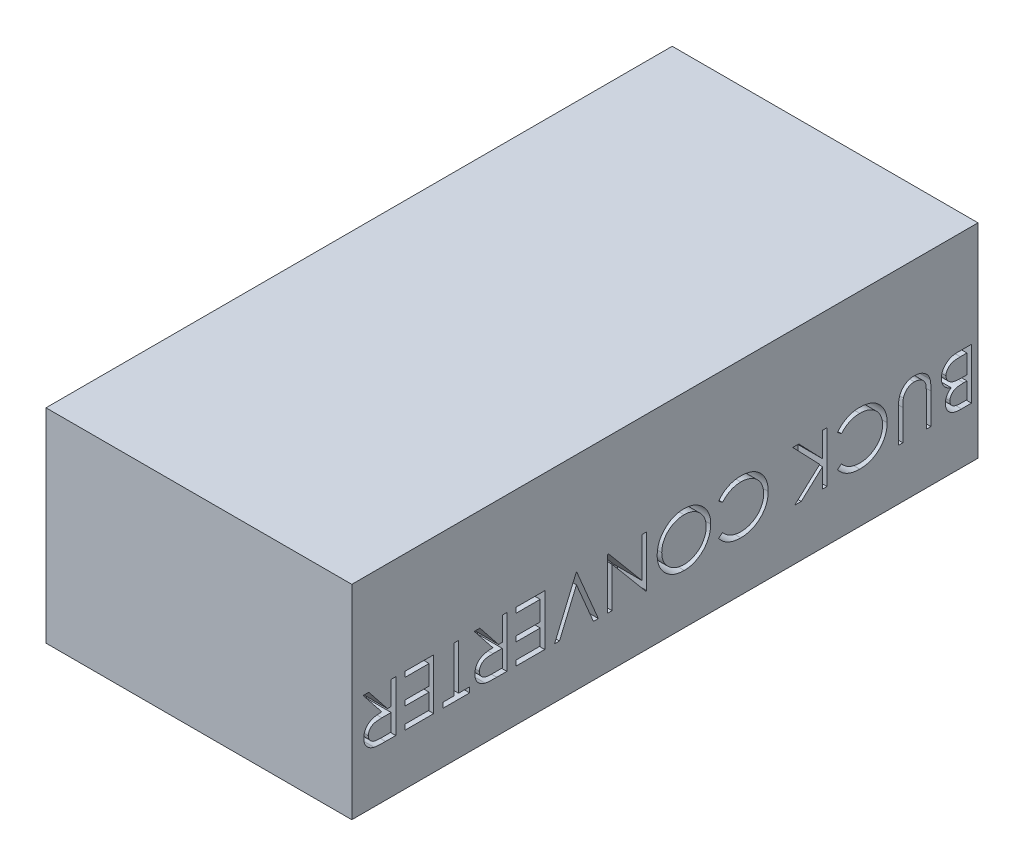
SolidWorks part; units mm, degrees
ref_plane "Front Plane" through (0, 0, 0) normal (0, 0, 1) x (1, 0, 0)
ref_plane "Top Plane" through (0, 0, 0) normal (0, 1, 0) x (1, 0, 0)
ref_plane "Right Plane" through (0, 0, 0) normal (1, 0, 0) x (0, 0, -1)
sketch "Sketch1" plane through (0, 0, 0) normal (0, 1, 0) x (1, 0, 0)
  line L1 (-10.5, -21.5) -> (10.5, -21.5)
  line L2 (-10.5, -21.5) -> (-10.5, 21.5)
  line L3 (-10.5, 21.5) -> (10.5, 21.5)
  line L4 (10.5, -21.5) -> (10.5, 21.5)
  line L5 (-10.5, -21.5) -> (10.5, 21.5) construction
  line L6 (-10.5, 21.5) -> (10.5, -21.5) construction
  point P0 (0, 0)
  dimension "D1" = 21
  dimension "D2" = 43
extrude "Boss-Extrude1" add sketch "Sketch1" along normal blind 14
sketch "Sketch2" plane through (10.5, 0, 0) normal (1, 0, 0) x (0, 0, -1)
  line L0 (21.5, 7) -> (-21.5, 7) construction
  line L1 (21.5, 14) -> (21.5, 0) construction
  line L2 (-21.5, 14) -> (-21.5, 0) construction
  text T0 "BUCK CONVERTER"
extrude "Cut-Extrude1" cut sketch "Sketch2" against normal blind 2
